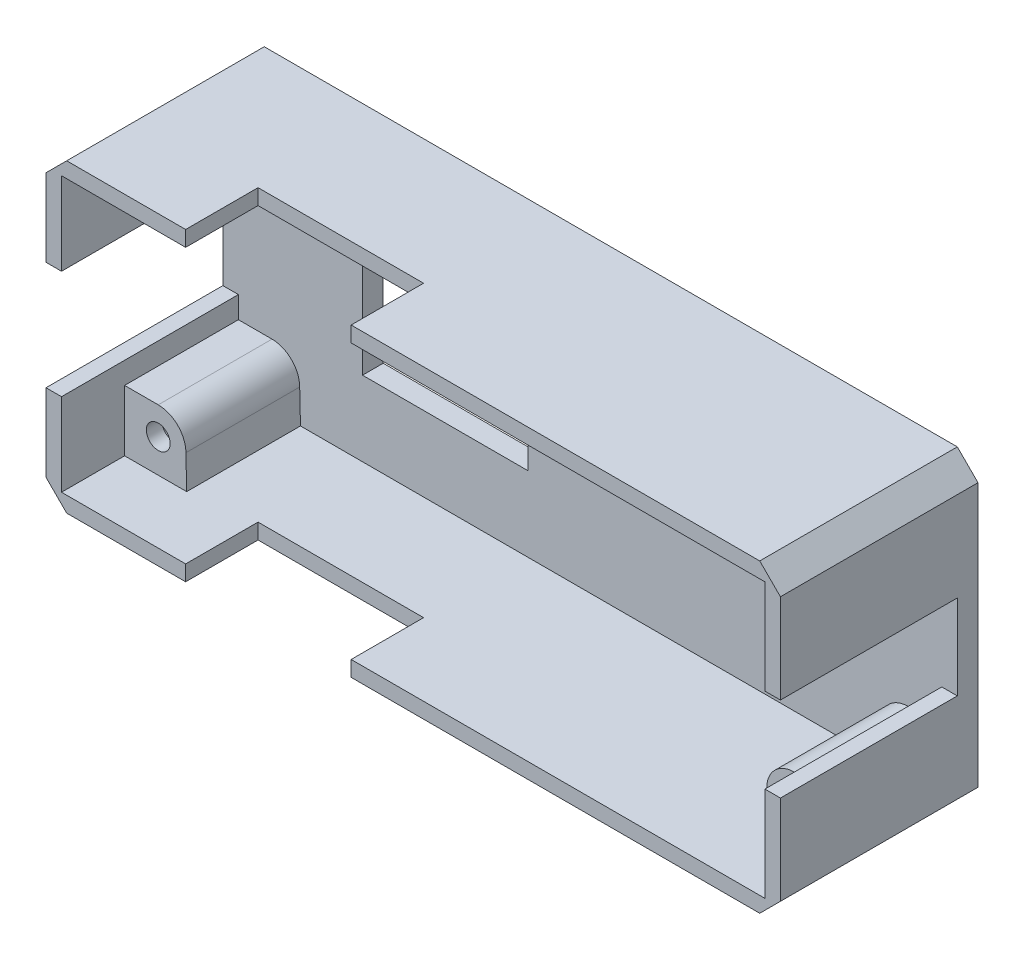
SolidWorks part; units mm, degrees
ref_plane "Front Plane" through (0, 0, 0) normal (0, 0, 1) x (1, 0, 0)
ref_plane "Top Plane" through (0, 0, 0) normal (0, 1, 0) x (1, 0, 0)
ref_plane "Right Plane" through (0, 0, 0) normal (1, 0, 0) x (0, 0, -1)
sketch "Sketch1" plane through (0, 0, 0) normal (0, 0, 1) x (1, 0, 0)
  line L0 (-14, 0) -> (0, 0) construction
  line L5 (-34, 13.25) -> (34, 13.25) construction
  line L6 (-34, 13.25) -> (-34, -13.25) construction
  line L7 (-34, -13.25) -> (34, -13.25) construction
  line L8 (34, 13.25) -> (34, -13.25) construction
  line L9 (-34, 13.25) -> (34, -13.25) construction
  line L10 (-34, -13.25) -> (34, 13.25) construction
  line L11 (-22, 6) -> (-6, 6)
  line L12 (-22, 6) -> (-22, -6)
  line L13 (-22, -6) -> (-6, -6)
  line L14 (-6, 6) -> (-6, -6)
  line L15 (-22, 6) -> (-6, -6) construction
  line L16 (-22, -6) -> (-6, 6) construction
  line L18 (35.5, -14.75) -> (-35.5, -14.75)
  line L19 (35.5, -14.75) -> (35.5, 14.75)
  line L20 (35.5, 14.75) -> (-35.5, 14.75)
  line L21 (-35.5, -14.75) -> (-35.5, 14.75)
  line L22 (35.5, -14.75) -> (-35.5, 14.75) construction
  line L23 (35.5, 14.75) -> (-35.5, -14.75) construction
  point P0 (-14, 0)
  point P1 (0, 0)
  point P12 (-14, -6)
  dimension "D1" = 12
  dimension "D2" = 16
  dimension "D3" = 26.5
  dimension "D4" = 68
  dimension "D5" = 12
  dimension "D6" = 71
  dimension "D7" = 29.5
extrude "Boss-Extrude2" add sketch "Sketch1" along normal blind 2
sketch "Sketch2" plane through (0, 0, 2) normal (0, 0, 1) x (1, 0, 0)
  line L0 (0, 0) -> (0, 11.3394) construction
  line L1 (0, 0) -> (-14.7037, 0) construction
  line L2 (34, 13.25) -> (34, -13.25) construction
  line L3 (-34, -13.25) -> (34, -13.25) construction
  line L4 (-34, 13.25) -> (-34, -13.25) construction
  line L5 (-34, 13.25) -> (34, 13.25) construction
  line L6 (34, 13.25) -> (34, 4.1)
  line L7 (-34, -13.25) -> (34, -13.25)
  line L8 (-34, 13.25) -> (-34, 5.25)
  line L9 (-34, 13.25) -> (34, 13.25)
  line L14 (-35.5, 5.25) -> (-34, 5.25)
  line L15 (-35.5, -5.25) -> (-34, -5.25)
  line L16 (-34, -5.25) -> (-34, -13.25)
  line L17 (-35.5, -5.25) -> (-35.5, -14.75)
  line L18 (-35.5, 14.75) -> (-35.5, -14.75)
  line L19 (-35.5, -14.75) -> (35.5, -14.75)
  line L20 (35.5, -14.75) -> (35.5, 14.75)
  line L21 (35.5, 14.75) -> (-35.5, 14.75)
  line L22 (-35.5, 14.75) -> (-35.5, 5.25)
  line L23 (-35.5, -14.75) -> (35.5, -14.75)
  line L24 (35.5, -14.75) -> (35.5, -4.1)
  line L25 (35.5, 14.75) -> (-35.5, 14.75)
  line L26 (34, 4.1) -> (35.5, 4.1)
  line L27 (34, -4.1) -> (35.5, -4.1)
  line L28 (34, -4.1) -> (34, -13.25)
  line L29 (35.5, 4.1) -> (35.5, 14.75)
  circle A0 centre (-30.75, 10.03) radius 1.15 construction
  circle A5 centre (-30.75, 10.03) radius 2.175 construction
  circle A10 centre (-30.75, 10.03) radius 2.675 construction
  dimension "D3" = 2.3
  dimension "D4" = 4.35
  dimension "D7" = 0
  dimension "D10" = 5.35
  dimension "D1" = 30.75
  dimension "D2" = 10.03
  dimension "D5" = 68
  dimension "D6" = 26.5
  dimension "D8" = 10.5
  dimension "D9" = 8.2
extrude "Boss-Extrude3" add sketch "Sketch2" along normal blind 17.1
sketch "Sketch3" plane through (0, -14.75, 0) normal (0, -1, 0) x (1, 0, 0)
  line L0 (-35.5, 19.1) -> (35.5, 19.1) construction
  line L1 (-22, 12.1) -> (-6, 12.1)
  line L2 (-22, 12.1) -> (-22, 19.1)
  line L3 (-22, 19.1) -> (-6, 19.1)
  line L4 (-6, 12.1) -> (-6, 19.1)
  line L5 (-35.5, 19.1) -> (-35.5, 0) construction
  dimension "D1" = 16
  dimension "D2" = 13.5
  dimension "D3" = 7
extrude "Cut-Extrude1" cut sketch "Sketch3" against normal through all
chamfer "Chamfer1" distance 2 angle 45 4 edges at (35.5, 14.75, 9.55) (35.5, -14.75, 9.55) (-35.5, -14.75, 9.55) (-35.5, 14.75, 9.55)
sketch "Sketch7" plane through (0, 0, 2) normal (0, 0, 1) x (1, 0, 0)
  line L0 (0, 0) -> (-14.7037, 0) construction
  line L1 (0, 0) -> (0, 11.3394) construction
  line L2 (0, 0) -> (-14.7037, 0) construction
  line L3 (0, 0) -> (0, 11.3394) construction
  line L4 (-34, 5.25) -> (-34, 13.25) construction
  line L5 (-34, 13.25) -> (34, 13.25) construction
  line L6 (-34, 10.3053) -> (-34, 13.25)
  line L7 (-34, 13.25) -> (-30.75, 13.25)
  line L37 (-30.75, 7.355) -> (-34, 7.355)
  line L38 (-34, 7.355) -> (-34, 10.3053)
  line L39 (-28.075, 10.03) -> (-28, 13.25)
  line L40 (-34, 13.25) -> (-22, 13.25) construction
  line L41 (-28, 13.25) -> (-30.75, 13.25)
  line L42 (28, 13.25) -> (30.75, 13.25)
  line L43 (28.075, 10.03) -> (28, 13.25)
  line L44 (34, 7.355) -> (34, 10.3053)
  line L45 (30.75, 7.355) -> (34, 7.355)
  line L46 (34, 13.25) -> (30.75, 13.25)
  line L47 (34, 10.3053) -> (34, 13.25)
  line L48 (-28, -13.25) -> (-30.75, -13.25)
  line L49 (-28.075, -10.03) -> (-28, -13.25)
  line L50 (-34, -7.355) -> (-34, -10.3053)
  line L51 (-30.75, -7.355) -> (-34, -7.355)
  line L52 (-34, -13.25) -> (-30.75, -13.25)
  line L53 (-34, -10.3053) -> (-34, -13.25)
  line L54 (34, -10.3053) -> (34, -13.25)
  line L55 (34, -13.25) -> (30.75, -13.25)
  line L56 (30.75, -7.355) -> (34, -7.355)
  line L57 (34, -7.355) -> (34, -10.3053)
  line L58 (28.075, -10.03) -> (28, -13.25)
  line L59 (28, -13.25) -> (30.75, -13.25)
  circle A0 centre (-30.75, 10.03) radius 2.675 construction
  arc A1 (-30.75, 7.355) -> (-28.075, 10.03) centre (-30.75, 10.03) ccw
  arc A8 (30.75, 7.355) -> (28.075, 10.03) centre (30.75, 10.03) cw
  arc A9 (-30.75, -7.355) -> (-28.075, -10.03) centre (-30.75, -10.03) cw
  arc A10 (30.75, -7.355) -> (28.075, -10.03) centre (30.75, -10.03) ccw
extrude "Boss-Extrude4" add sketch "Sketch7" along normal blind 11
sketch "Sketch8" plane through (0, 0, 0) normal (0, 0, -1) x (-1, 0, 0)
  line L0 (0, 0) -> (0, 11.3394) construction
  line L1 (0, 0) -> (14.7037, 0) construction
  line L2 (0, 0) -> (14.7037, 0) construction
  line L3 (0, 0) -> (0, 11.3394) construction
  circle A0 centre (30.75, 10.03) radius 1.15 construction
  circle A1 centre (30.75, 10.03) radius 1.15
  circle A2 centre (-30.75, 10.03) radius 1.15
  circle A3 centre (-30.75, -10.03) radius 1.15
  circle A4 centre (30.75, -10.03) radius 1.15
  dimension "D1" = 2.3
extrude "Cut-Extrude3" cut sketch "Sketch8" against normal through all
sketch "Sketch9" plane through (0, 0, 0) normal (0, 0, -1) x (-1, 0, 0)
  line L0 (0, 0) -> (14.7037, 0) construction
  line L1 (0, 0) -> (0, 11.3394) construction
  line L2 (0, 0) -> (14.7037, 0) construction
  line L3 (0, -11.3394) -> (0, 11.3394) construction
  circle A0 centre (30.75, 10.03) radius 2.175 construction
  circle A1 centre (30.75, 10.03) radius 2.175
  circle A2 centre (-30.75, 10.03) radius 2.175
  circle A3 centre (-30.75, -10.03) radius 2.175
  circle A4 centre (30.75, -10.03) radius 2.175
extrude "Cut-Extrude4" cut sketch "Sketch9" against normal offset from surface (11.5 mm away) 1.5 up to face at (-29.6, 10.03, 13)
